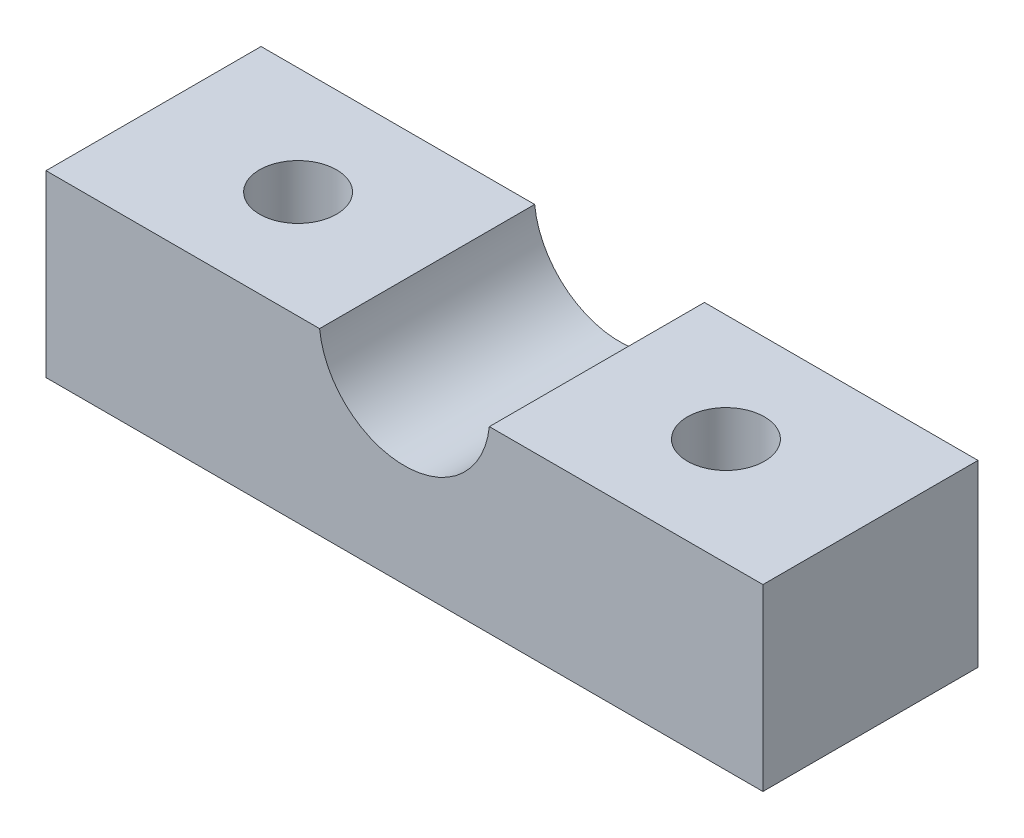
SolidWorks part; units mm, degrees
ref_plane "Front Plane" through (0, 0, 0) normal (0, 0, 1) x (1, 0, 0)
ref_plane "Top Plane" through (0, 0, 0) normal (0, 1, 0) x (1, 0, 0)
ref_plane "Right Plane" through (0, 0, 0) normal (1, 0, 0) x (0, 0, -1)
sketch "Sketch1" plane through (0, 0, 0) normal (0, 0, 1) x (1, 0, 0)
  line L0 (0, 10.5) -> (0, 0) construction
  line L1 (20, 0) -> (-20, 0)
  line L2 (20, 0) -> (20, 10)
  line L3 (20, 10) -> (4.7362, 10)
  line L4 (-20, 0) -> (-20, 10)
  line L5 (-4.7362, 10) -> (-20, 10)
  arc A0 (-4.7362, 10) -> (4.7362, 10) centre (0, 10.5) ccw
  dimension "D2" = 9.525
  dimension "D1" = 40
  dimension "D3" = 0.5
  dimension "D4" = 10
extrude "Boss-Extrude1" add sketch "Sketch1" along normal mid plane 12
sketch "Sketch2" plane through (0, 0, 0) normal (0, -1, 0) x (1, 0, 0)
  line L0 (-11.9365, 0) -> (11.9365, 0) construction
  dimension "D1" = 23.873
hole_wizard "CBORE for M4 SHCS1" positions "Sketch4" profile "Sketch3" counterbore size "M4" standard "Ansi Metric" end condition through all
sketch "Sketch4" plane through (0, 0, 0) normal (0, -1, 0) x (1, 0, 0)
  point P0 (-11.9365, 0)
  point P1 (11.9365, 0)
sketch "Sketch3" plane through (-11.9365, 0, 0) normal (1, 0, 0) x (0, 0, -1)
  line L0 (0, 0) -> (0, 10)
  line L1 (0, 10) -> (2.15, 10)
  line L3 (2.15, 10) -> (2.15, 4)
  line L4 (2.15, 4) -> (4, 4)
  line L5 (4, 4) -> (4, 0)
  line L7 (4, 0) -> (0, 0)
  line L11 (0, -6.35) -> (0, 107.95) construction
  dimension "Thru Hole Dia." = 4.3
  dimension "Thru Hole Depth" = 10
  dimension "C'Bore Dia." = 8
  dimension "C'Bore Depth" = 4
